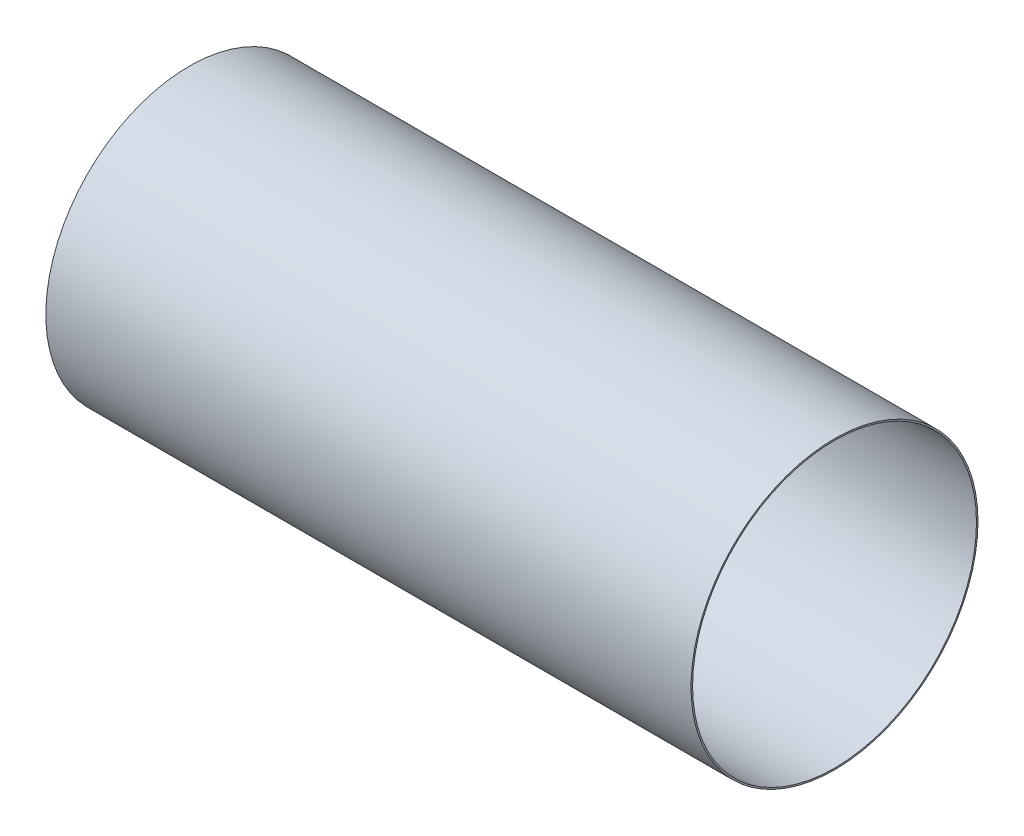
SolidWorks part; units mm, degrees
material "6061 Alloy"
ref_plane "Front Plane" through (0, 0, 0) normal (0, 0, 1) x (1, 0, 0)
ref_plane "Top Plane" through (0, 0, 0) normal (0, 1, 0) x (1, 0, 0)
ref_plane "Right Plane" through (0, 0, 0) normal (1, 0, 0) x (0, 0, -1)
sketch "Sketch1" plane through (0, 0, 0) normal (1, 0, 0) x (0, 0, -1)
  circle A0 centre (0, 0) radius 27.94
  circle A1 centre (0, 0) radius 28.24
  dimension "D1" = 55.88
  dimension "D2" = 0.3
extrude "Boss-Extrude1" add sketch "Sketch1" along normal blind 127
